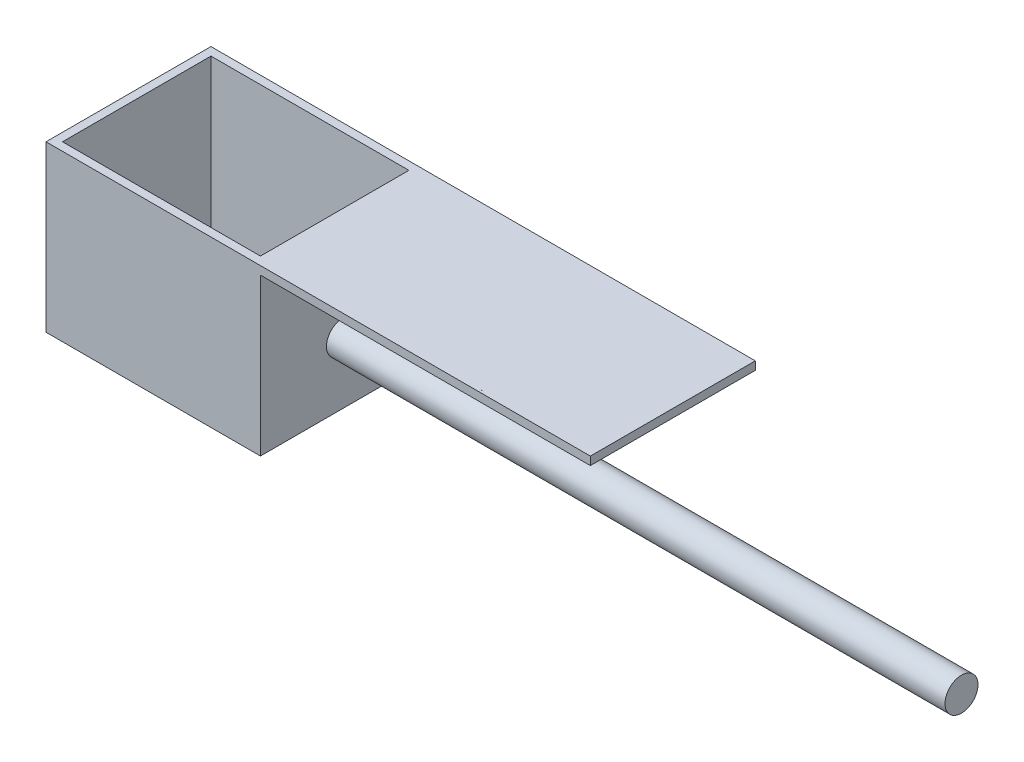
SolidWorks part; units mm, degrees
material "Cast Alloy Steel"
ref_plane "Front Plane" through (0, 0, 0) normal (0, 0, 1) x (1, 0, 0)
ref_plane "Top Plane" through (0, 0, 0) normal (0, 1, 0) x (1, 0, 0)
ref_plane "Right Plane" through (0, 0, 0) normal (1, 0, 0) x (0, 0, -1)
sketch "Sketch1" plane through (0, 0, 0) normal (0, 1, 0) x (1, 0, 0)
  line L0 (2, -2) -> (50, -2)
  line L1 (0, 0) -> (52, 0)
  line L2 (0, 0) -> (0, -40)
  line L3 (0, -40) -> (52, -40)
  line L4 (52, 0) -> (52, -40)
  line L5 (50, -2) -> (50, -38)
  line L6 (2, -38) -> (50, -38)
  line L7 (2, -2) -> (2, -38)
  dimension "D1" = 52
  dimension "D3" = 40
  dimension "D2" = 2
extrude "Boss-Extrude1" add sketch "Sketch1" along normal blind 40
sketch "Sketch2" plane through (52, 0, 0) normal (1, 0, 0) x (0, 0, -1)
  line L0 (0, 40) -> (0, 0) construction
  line L1 (-40, 40) -> (0, 40)
  line L2 (-40, 40) -> (-40, 38)
  line L3 (-40, 38) -> (0, 38)
  line L4 (0, 40) -> (0, 38)
  dimension "D1" = 2
extrude "Boss-Extrude2" add sketch "Sketch2" along normal blind 80
sketch "Sketch3" plane through (52, 0, 0) normal (1, 0, 0) x (0, 0, -1)
  line L0 (-20, 0) -> (-20, 38) construction
  line L1 (-40, 0) -> (0, 0) construction
  line L2 (-40, 38) -> (0, 38) construction
  circle A0 centre (-20, 15) radius 4
  dimension "D1" = 8
  dimension "D2" = 15
extrude "Boss-Extrude3" add sketch "Sketch3" along normal blind 150
